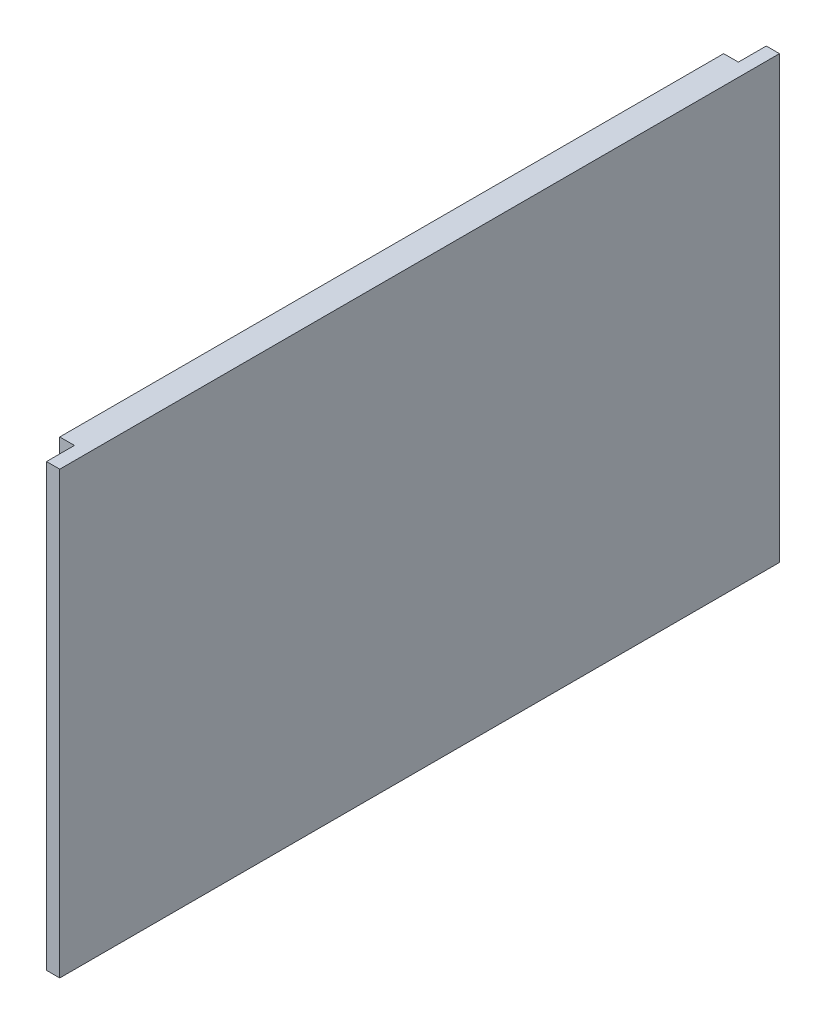
SolidWorks part; units mm, degrees
ref_plane "Front Plane" through (0, 0, 0) normal (0, 0, 1) x (1, 0, 0)
ref_plane "Top Plane" through (0, 0, 0) normal (0, 1, 0) x (1, 0, 0)
ref_plane "Right Plane" through (0, 0, 0) normal (1, 0, 0) x (0, 0, -1)
sketch "Sketch1" plane through (0, 0, 0) normal (1, 0, 0) x (0, 0, -1)
  line L1 (0, 0) -> (490, 0)
  line L2 (0, 0) -> (0, 300)
  line L3 (0, 300) -> (490, 300)
  line L4 (490, 0) -> (490, 300)
  dimension "D1" = 490
  dimension "D2" = 300
extrude "Boss-Extrude1" add sketch "Sketch1" along normal blind 19
sketch "Sketch5" plane through (0, 0, 0) normal (0, 0, 1) x (1, 0, 0)
  line L0 (19, 0) -> (0, 0) construction
  line L1 (0, 300) -> (10, 300)
  line L2 (0, 300) -> (0, 0)
  line L3 (0, 0) -> (10, 0)
  line L4 (10, 300) -> (10, 0)
  dimension "D1" = 10
extrude "Cut-Extrude1" cut sketch "Sketch5" against normal blind 19
sketch "Sketch6" plane through (0, 0, 0) normal (-1, 0, 0) x (0, 0, 1)
  line L0 (-19, 0) -> (-490, 0) construction
  line L1 (-490, 300) -> (-471, 300)
  line L2 (-490, 300) -> (-490, 0)
  line L3 (-490, 0) -> (-471, 0)
  line L4 (-471, 300) -> (-471, 0)
  dimension "D1" = 19
extrude "Cut-Extrude3" cut sketch "Sketch6" against normal blind 10
